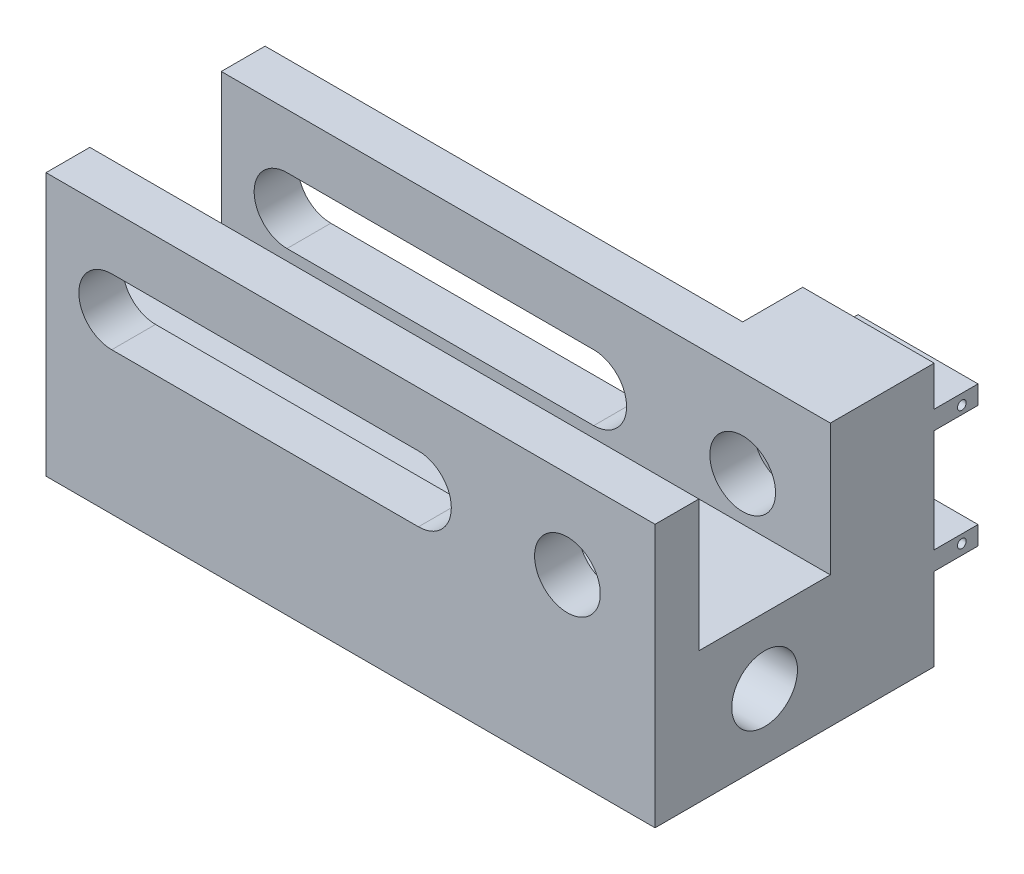
SolidWorks part; units mm, degrees
ref_plane "Front Plane" through (0, 0, 0) normal (0, 0, 1) x (1, 0, 0)
ref_plane "Top Plane" through (0, 0, 0) normal (0, 1, 0) x (1, 0, 0)
ref_plane "Right Plane" through (0, 0, 0) normal (1, 0, 0) x (0, 0, -1)
sketch "Sketch2" plane through (0, 0, 0) normal (1, 0, 0) x (0, 0, -1)
  line L0 (-15, 30) -> (15, 30)
  line L2 (-25, 0) -> (25, 0)
  line L3 (25, 51.1347) -> (25, 0)
  line L5 (-25, 60) -> (-15, 60)
  line L6 (-15, 30) -> (-15, 60)
  line L7 (25, 51.1347) -> (25, 60)
  line L8 (25, 60) -> (15, 60)
  line L9 (15, 30) -> (15, 60)
  line L10 (-25, 60) -> (-25, 0)
  point P4 (0, 0)
  dimension "D1" = 50
  dimension "D2" = 10
  dimension "D3" = 10
  dimension "D4" = 30
  dimension "D5" = 30
  dimension "D6" = 30
extrude "Boss-Extrude1" add sketch "Sketch2" along normal blind 139
sketch "Sketch3" plane through (0, 0, -25) normal (0, 0, -1) x (-1, 0, 0)
  line L0 (-85, 40) -> (-15, 40) construction
  line L1 (-85, 47.5) -> (-15, 47.5)
  line L2 (-85, 32.5) -> (-15, 32.5)
  line L3 (-139, 0) -> (-139, 60) construction
  line L4 (-139, 60) -> (0, 60) construction
  line L5 (0, 0) -> (0, 60) construction
  circle A0 centre (-119, 40) radius 7.5
  arc A1 (-85, 47.5) -> (-85, 32.5) centre (-85, 40) ccw
  arc A2 (-15, 32.5) -> (-15, 47.5) centre (-15, 40) ccw
  point P2 (-50, 40)
  dimension "D1" = 15
  dimension "D2" = 15
  dimension "D3" = 70
  dimension "D4" = 20
  dimension "D5" = 20
  dimension "D6" = 15
extrude "Cut-Extrude1" cut sketch "Sketch3" against normal through all
sketch "Sketch4" plane through (139, 0, 0) normal (1, 0, 0) x (0, 0, -1)
  line L0 (-25, 60) -> (-25, 0) construction
  line L2 (-25, 0) -> (25, 0) construction
  circle A0 centre (0, 15) radius 7.5
  dimension "D1" = 15
  dimension "D2" = 25
  dimension "D3" = 15
extrude "Cut-Extrude2" cut sketch "Sketch4" against normal through all both and the other way through all
sketch "Sketch5" plane through (0, 0, -25) normal (0, 0, -1) x (-1, 0, 0)
  line L0 (-139, 0) -> (-139, 60) construction
  line L7 (-139, 0) -> (-109, 0)
  line L8 (-139, 0) -> (-139, 60)
  line L9 (-139, 60) -> (-109, 60)
  line L10 (-109, 0) -> (-109, 60)
  line L11 (-139, 60) -> (0, 60) construction
  point P8 (-104.7323, 19.4607)
  dimension "D1" = 30
  dimension "D2" = 60
extrude "Boss-Extrude2" add sketch "Sketch5" along normal blind 13.7
sketch "Sketch6" plane through (0, 0, -38.7) normal (0, 0, -1) x (-1, 0, 0)
  line L0 (-139, 60) -> (-139, 0) construction
  line L1 (-139, 50.9) -> (-111.6177, 50.9)
  line L2 (-139, 50.9) -> (-139, 46.65)
  line L3 (-139, 46.65) -> (-111.6177, 46.65)
  line L4 (-111.6177, 50.9) -> (-111.6177, 46.65)
  line L5 (-111.2177, 50.9) -> (-111.2177, 49.3128) construction
  line L6 (-111.2177, 46.25) -> (-111.2177, 53.3831)
  line L7 (-126.9011, 23.5) -> (-139, 23.5) construction
  line L8 (-139, 46.25) -> (-111.2177, 46.25) construction
  line L9 (-111.2177, 46.25) -> (-124.4677, 46.25) construction
  line L10 (-111.2177, 50.9) -> (-108.8677, 50.9) construction
  line L11 (-139, 18.85) -> (-111.4177, 18.85)
  line L12 (-139, 18.85) -> (-139, 23.1)
  line L13 (-139, 23.1) -> (-111.4177, 23.1)
  line L14 (-111.4177, 18.85) -> (-111.4177, 23.1)
  line L15 (-124.4677, 23.5) -> (-111.2177, 23.5) construction
  line L16 (-111.2177, 14.5051) -> (-111.2177, 25.8744) construction
  line L17 (-111.2177, 22.175) -> (-111.2177, 20.4372) construction
  line L18 (-111.2177, 18.85) -> (-108.8677, 18.85) construction
  line M11 (-139, 60) -> (-139, 0)
  dimension "D1" = 0.4
  dimension "D2" = 0.4
  dimension "D3" = 0.4
  dimension "D4" = 0.4
extrude "Boss-Extrude3" add sketch "Sketch6" along normal blind 10 contours L11 L14 L13 M11 | L4 L1 L3 M11
sketch "Sketch7" plane through (111.6177, 0, 0) normal (-1, 0, 0) x (0, 0, 1)
  circle A0 centre (-45.0132, 48.5294) radius 1
  circle A1 centre (-45.0132, 21.1907) radius 1
  point P2 (-45.0132, 21.1907)
extrude "Cut-Extrude3" cut sketch "Sketch7" against normal through all both and the other way through all
